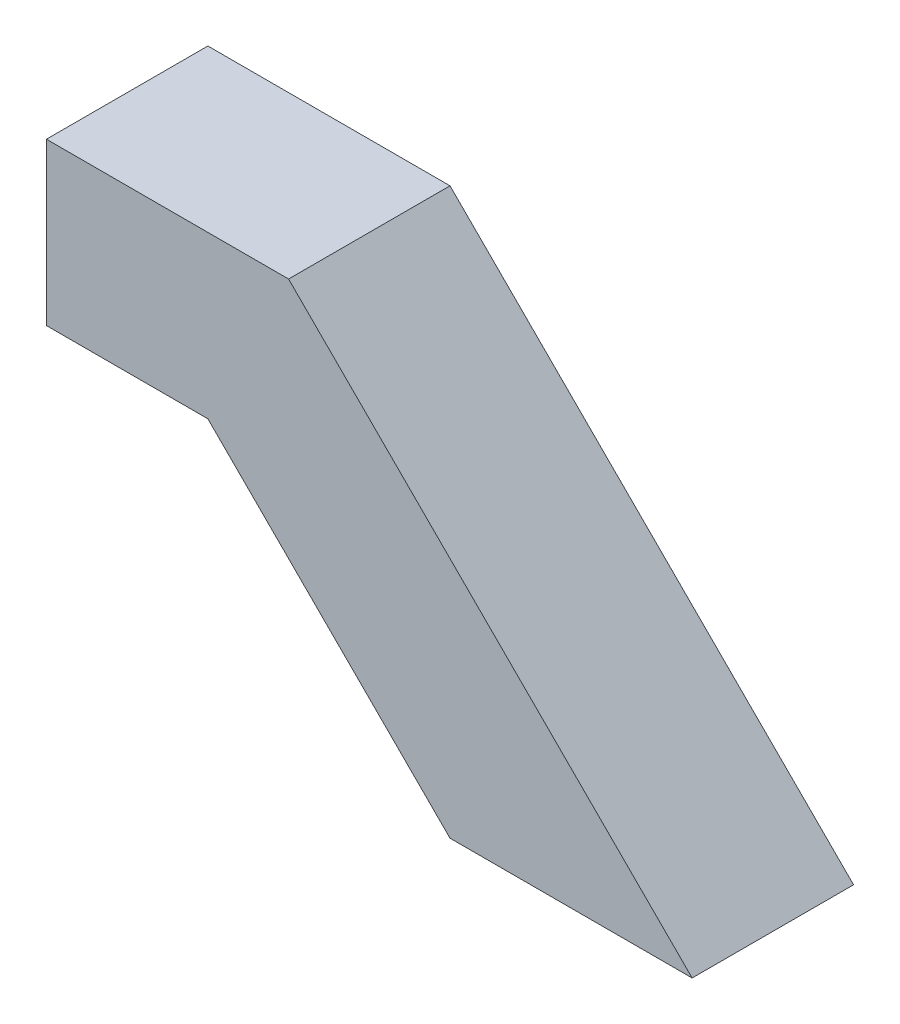
SolidWorks part; units mm, degrees
ref_plane "Front Plane" through (0, 0, 0) normal (0, 0, 1) x (1, 0, 0)
ref_plane "Top Plane" through (0, 0, 0) normal (0, 1, 0) x (1, 0, 0)
ref_plane "Right Plane" through (0, 0, 0) normal (1, 0, 0) x (0, 0, -1)
sketch "Sketch1" plane through (0, 0, 0) normal (0, 0, 1) x (1, 0, 0)
  line L0 (0, 0) -> (0, 20)
  line L1 (0, 20) -> (30, 20)
  line L2 (30, 20) -> (80, -30)
  line L3 (80, -30) -> (50, -30)
  line L4 (0, 0) -> (20, 0)
  line L5 (20, 0) -> (50, -30)
  dimension "D1" = 20
  dimension "D2" = 30
  dimension "D3" = 135
  dimension "D4" = 30
  dimension "D5" = 20
extrude "Boss-Extrude1" add sketch "Sketch1" along normal blind 20
